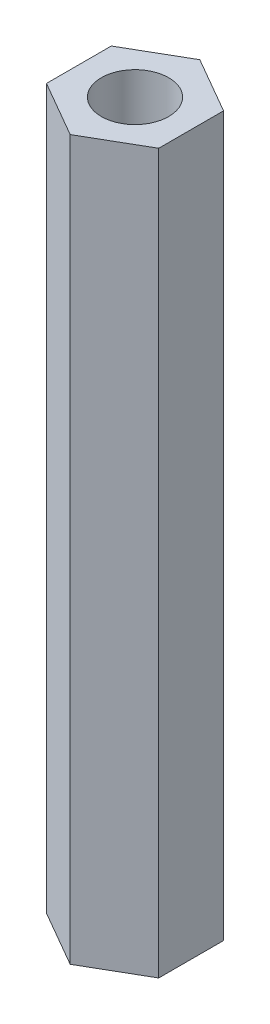
SolidWorks part; units mm, degrees
ref_plane "前基準面" through (0, 0, 0) normal (0, 0, 1) x (1, 0, 0)
ref_plane "上基準面" through (0, 0, 0) normal (0, 1, 0) x (1, 0, 0)
ref_plane "右基準面" through (0, 0, 0) normal (1, 0, 0) x (0, 0, -1)
sketch "草圖1" plane through (0, 0, 0) normal (0, 1, 0) x (1, 0, 0)
  line L1 (0, 2.8868) -> (-2.5, 1.4434)
  line L2 (-2.5, 1.4434) -> (-2.5, -1.4434)
  line L3 (-2.5, -1.4434) -> (0, -2.8868)
  line L4 (0, -2.8868) -> (2.5, -1.4434)
  line L5 (2.5, -1.4434) -> (2.5, 1.4434)
  line L6 (2.5, 1.4434) -> (0, 2.8868)
  circle A0 centre (0, 0) radius 2.5 construction
  dimension "D1" = 5
extrude "填料-伸長1" add sketch "草圖1" along normal blind 32
sketch "草圖2" plane through (0, 32, 0) normal (0, 1, 0) x (-1, 0, 0)
  circle A0 centre (0, 0) radius 1.5
  dimension "D1" = 3
extrude "除料-伸長1" cut sketch "草圖2" against normal up to next
